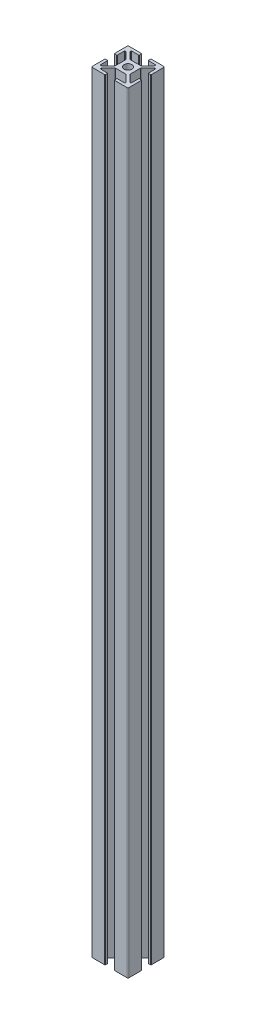
SolidWorks part; units mm, degrees
ref_plane "Спереди" through (0, 0, 0) normal (0, 0, 1) x (1, 0, 0)
ref_plane "Сверху" through (0, 0, 0) normal (0, 1, 0) x (1, 0, 0)
ref_plane "Справа" through (0, 0, 0) normal (1, 0, 0) x (0, 0, -1)
sketch "Эскиз1" plane through (0, 0, 210) normal (0, -1, 0) x (1, 0, 0)
  line L0 (-10, -2.75) -> (-10, -9.5)
  line L1 (-9.5, -10) -> (-2.75, -10)
  line L2 (-2.5, -9.75) -> (-2.5, -8.75)
  line L3 (-2.75, -8.5) -> (-6.5, -8.5)
  line L4 (-6.75, -8.25) -> (-6.75, -7.9142)
  line L5 (-6.6768, -7.7374) -> (-3.0858, -4.1464)
  line L6 (-2.7322, -4) -> (2.7322, -4)
  line L7 (3.0858, -4.1464) -> (6.6768, -7.7374)
  line L8 (6.75, -7.9142) -> (6.75, -8.25)
  line L9 (6.5, -8.5) -> (2.75, -8.5)
  line L10 (2.5, -8.75) -> (2.5, -9.75)
  line L11 (2.75, -10) -> (9.5, -10)
  line L12 (10, -9.5) -> (10, -2.75)
  line L13 (9.75, -2.5) -> (8.75, -2.5)
  line L14 (8.5, -2.75) -> (8.5, -6.5)
  line L15 (8.25, -6.75) -> (7.9142, -6.75)
  line L16 (7.7374, -6.6768) -> (4.1464, -3.0858)
  line L17 (4, -2.7322) -> (4, 2.7322)
  line L18 (4.1464, 3.0858) -> (7.7374, 6.6768)
  line L19 (7.9142, 6.75) -> (8.25, 6.75)
  line L20 (8.5, 6.5) -> (8.5, 2.75)
  line L21 (8.75, 2.5) -> (9.75, 2.5)
  line L22 (10, 2.75) -> (10, 9.5)
  line L23 (9.5, 10) -> (2.75, 10)
  line L24 (2.5, 9.75) -> (2.5, 8.75)
  line L25 (2.75, 8.5) -> (6.5, 8.5)
  line L26 (6.75, 8.25) -> (6.75, 7.8107)
  line L27 (6.75, 7.8107) -> (3.0126, 4.0732)
  line L28 (2.8358, 4) -> (-2.7322, 4)
  line L29 (-3.0858, 4.1464) -> (-6.6768, 7.7374)
  line L30 (-6.75, 7.9142) -> (-6.75, 8.25)
  line L31 (-6.5, 8.5) -> (-2.75, 8.5)
  line L32 (-2.5, 8.75) -> (-2.5, 9.75)
  line L33 (-2.75, 10) -> (-9.5, 10)
  line L34 (-10, 9.5) -> (-10, 2.75)
  line L35 (-9.75, 2.5) -> (-8.75, 2.5)
  line L36 (-8.5, 2.75) -> (-8.5, 6.5)
  line L37 (-8.25, 6.75) -> (-7.9142, 6.75)
  line L38 (-7.7374, 6.6768) -> (-4.1464, 3.0858)
  line L39 (-4, 2.7322) -> (-4, -2.7322)
  line L40 (-4.1464, -3.0858) -> (-7.7374, -6.6768)
  line L41 (-7.9142, -6.75) -> (-8.25, -6.75)
  line L42 (-8.5, -6.5) -> (-8.5, -2.75)
  line L43 (-8.75, -2.5) -> (-9.75, -2.5)
  circle A0 centre (0, 0) radius 2.15
  arc A1 (-10, -9.5) -> (-9.5, -10) centre (-9.5, -9.5) ccw
  arc A2 (-2.75, -10) -> (-2.5, -9.75) centre (-2.75, -9.75) ccw
  arc A3 (-2.5, -8.75) -> (-2.75, -8.5) centre (-2.75, -8.75) ccw
  arc A4 (-6.5, -8.5) -> (-6.75, -8.25) centre (-6.5, -8.25) cw
  arc A5 (-6.75, -7.9142) -> (-6.6768, -7.7374) centre (-6.5, -7.9142) cw
  arc A6 (-3.0858, -4.1464) -> (-2.7322, -4) centre (-2.7322, -4.5) cw
  arc A7 (2.7322, -4) -> (3.0858, -4.1464) centre (2.7322, -4.5) cw
  arc A8 (6.6768, -7.7374) -> (6.75, -7.9142) centre (6.5, -7.9142) cw
  arc A9 (6.75, -8.25) -> (6.5, -8.5) centre (6.5, -8.25) cw
  arc A10 (2.75, -8.5) -> (2.5, -8.75) centre (2.75, -8.75) ccw
  arc A11 (2.5, -9.75) -> (2.75, -10) centre (2.75, -9.75) ccw
  arc A12 (9.5, -10) -> (10, -9.5) centre (9.5, -9.5) ccw
  arc A13 (10, -2.75) -> (9.75, -2.5) centre (9.75, -2.75) ccw
  arc A14 (8.75, -2.5) -> (8.5, -2.75) centre (8.75, -2.75) ccw
  arc A15 (8.5, -6.5) -> (8.25, -6.75) centre (8.25, -6.5) cw
  arc A16 (7.9142, -6.75) -> (7.7374, -6.6768) centre (7.9142, -6.5) cw
  arc A17 (4.1464, -3.0858) -> (4, -2.7322) centre (4.5, -2.7322) cw
  arc A18 (4, 2.7322) -> (4.1464, 3.0858) centre (4.5, 2.7322) cw
  arc A19 (7.7374, 6.6768) -> (7.9142, 6.75) centre (7.9142, 6.5) cw
  arc A20 (8.25, 6.75) -> (8.5, 6.5) centre (8.25, 6.5) cw
  arc A21 (8.5, 2.75) -> (8.75, 2.5) centre (8.75, 2.75) ccw
  arc A22 (9.75, 2.5) -> (10, 2.75) centre (9.75, 2.75) ccw
  arc A23 (10, 9.5) -> (9.5, 10) centre (9.5, 9.5) ccw
  arc A24 (2.75, 10) -> (2.5, 9.75) centre (2.75, 9.75) ccw
  arc A25 (2.5, 8.75) -> (2.75, 8.5) centre (2.75, 8.75) ccw
  arc A26 (6.5, 8.5) -> (6.75, 8.25) centre (6.5, 8.25) cw
  arc A27 (3.0126, 4.0732) -> (2.8358, 4) centre (2.8358, 4.25) cw
  arc A28 (-2.7322, 4) -> (-3.0858, 4.1464) centre (-2.7322, 4.5) cw
  arc A29 (-6.6768, 7.7374) -> (-6.75, 7.9142) centre (-6.5, 7.9142) cw
  arc A30 (-6.75, 8.25) -> (-6.5, 8.5) centre (-6.5, 8.25) cw
  arc A31 (-2.75, 8.5) -> (-2.5, 8.75) centre (-2.75, 8.75) ccw
  arc A32 (-2.5, 9.75) -> (-2.75, 10) centre (-2.75, 9.75) ccw
  arc A33 (-9.5, 10) -> (-10, 9.5) centre (-9.5, 9.5) ccw
  arc A34 (-10, 2.75) -> (-9.75, 2.5) centre (-9.75, 2.75) ccw
  arc A35 (-8.75, 2.5) -> (-8.5, 2.75) centre (-8.75, 2.75) ccw
  arc A36 (-8.5, 6.5) -> (-8.25, 6.75) centre (-8.25, 6.5) cw
  arc A37 (-7.9142, 6.75) -> (-7.7374, 6.6768) centre (-7.9142, 6.5) cw
  arc A38 (-4.1464, 3.0858) -> (-4, 2.7322) centre (-4.5, 2.7322) cw
  arc A39 (-4, -2.7322) -> (-4.1464, -3.0858) centre (-4.5, -2.7322) cw
  arc A40 (-7.7374, -6.6768) -> (-7.9142, -6.75) centre (-7.9142, -6.5) cw
  arc A41 (-8.25, -6.75) -> (-8.5, -6.5) centre (-8.25, -6.5) cw
  arc A42 (-8.5, -2.75) -> (-8.75, -2.5) centre (-8.75, -2.75) ccw
  arc A43 (-9.75, -2.5) -> (-10, -2.75) centre (-9.75, -2.75) ccw
extrude "Бобышка-Вытянуть1" add sketch "Эскиз1" against normal blind 420
